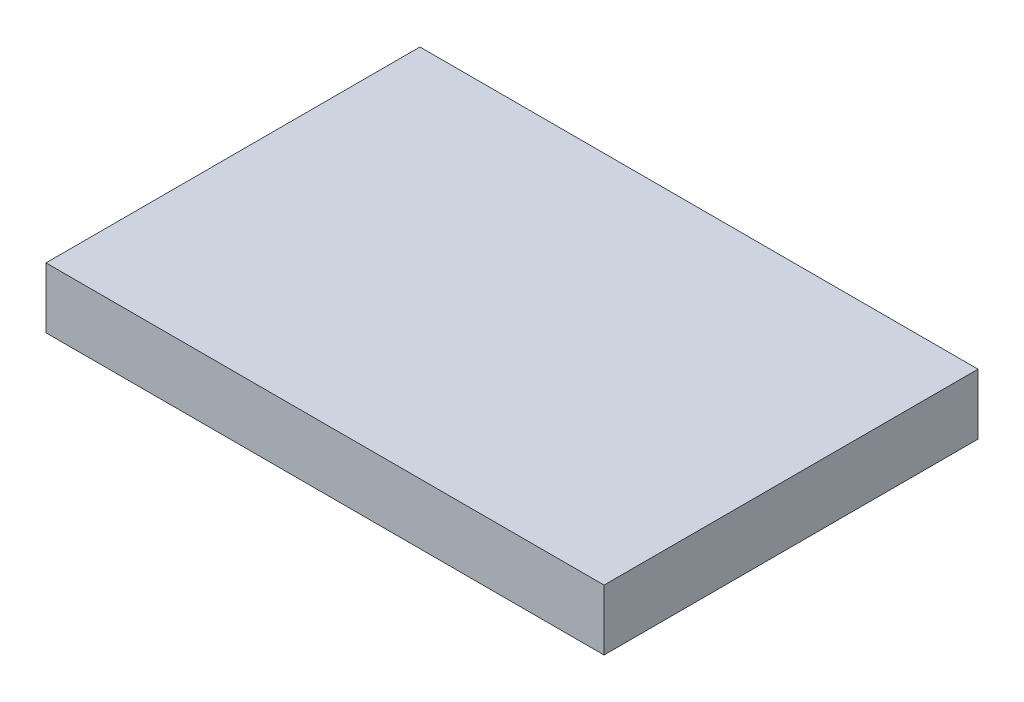
SolidWorks part; units mm, degrees
ref_plane "Front Plane" through (0, 0, 0) normal (0, 0, 1) x (1, 0, 0)
ref_plane "Top Plane" through (0, 0, 0) normal (0, 1, 0) x (1, 0, 0)
ref_plane "Right Plane" through (0, 0, 0) normal (1, 0, 0) x (0, 0, -1)
sketch "Sketch1" plane through (0, 0, 0) normal (0, 1, 0) x (1, 0, 0)
  line L1 (-41.45, -27.775) -> (41.45, -27.775)
  line L2 (-41.45, -27.775) -> (-41.45, 27.775)
  line L3 (-41.45, 27.775) -> (41.45, 27.775)
  line L4 (41.45, -27.775) -> (41.45, 27.775)
  line L5 (-41.45, -27.775) -> (41.45, 27.775) construction
  line L6 (-41.45, 27.775) -> (41.45, -27.775) construction
  point P0 (0, 0)
  dimension "D1" = 82.9
  dimension "D2" = 55.55
extrude "Boss-Extrude1" add sketch "Sketch1" along normal blind 9
